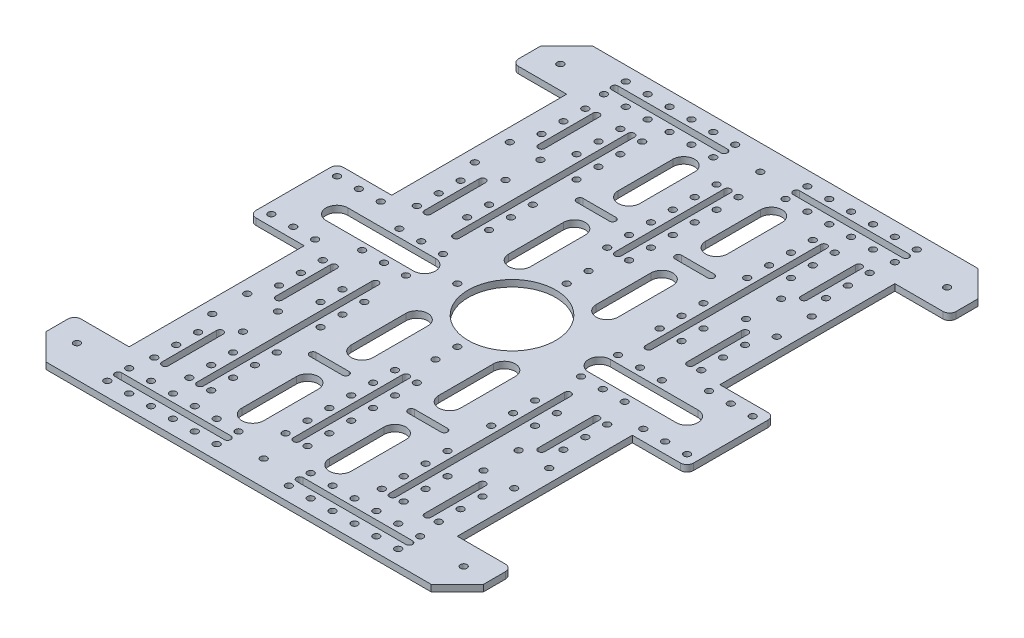
SolidWorks part; units mm, degrees
ref_plane "Front Plane" through (0, 0, 0) normal (0, 0, 1) x (1, 0, 0)
ref_plane "Top Plane" through (0, 0, 0) normal (0, 1, 0) x (1, 0, 0)
ref_plane "Right Plane" through (0, 0, 0) normal (1, 0, 0) x (0, 0, -1)
sketch "Sketch1" plane through (0, 0, 0) normal (0, 1, 0) x (1, 0, 0)
  line L0 (-100, 113) -> (-88, 125)
  line L1 (-88, 125) -> (88, 125)
  line L2 (-100, 113) -> (-100, 103)
  line L3 (-88, -125) -> (88, -125)
  line L4 (100, 113) -> (100, 103)
  line L5 (-75, 60) -> (-45.5, 60) construction
  line L7 (-100, -113) -> (-88, -125)
  line L8 (88, 125) -> (100, 113)
  line L9 (88, -125) -> (100, -113)
  line L10 (0, 125) -> (0, -125) construction
  line L11 (-100, 0) -> (100, 0) construction
  line L12 (-66.5, 113.5) -> (-16.5, 113.5) construction
  line L13 (-66.5, 115) -> (-16.5, 115)
  line L14 (-66.5, 112) -> (-16.5, 112)
  line L15 (0, 98.5) -> (0, 48.5) construction
  line L16 (1.5, 98.5) -> (1.5, 48.5)
  line L17 (-1.5, 98.5) -> (-1.5, 48.5)
  line L18 (-44, 98.5) -> (-44, 18.5) construction
  line L19 (-97, 100) -> (-75, 100)
  line L21 (-97, 20) -> (-75, 20)
  line L22 (-75, 100) -> (-75, 20)
  line L23 (-42.5, 98.5) -> (-42.5, 18.5)
  line L24 (-45.5, 98.5) -> (-45.5, 18.5)
  line L25 (-20, 98.5) -> (-20, 73.5) construction
  line L26 (-15, 98.5) -> (-15, 73.5)
  line L27 (-25, 98.5) -> (-25, 73.5)
  line L28 (-20, 48.5) -> (-20, 23.5) construction
  line L29 (-15, 48.5) -> (-15, 23.5)
  line L30 (-25, 48.5) -> (-25, 23.5)
  line L31 (-80, 0) -> (-40, 0) construction
  line L32 (-80, 5) -> (-40, 5)
  line L33 (-80, -5) -> (-40, -5)
  line L34 (-30, 61) -> (-15, 61) construction
  line L37 (-30, 62.5) -> (-15, 62.5)
  line L38 (-30, 59.5) -> (-15, 59.5)
  line L39 (100, 17) -> (100, -17)
  line L40 (-60, 98.5) -> (-60, 73.5) construction
  line L41 (-58.5, 98.5) -> (-58.5, 73.5)
  line L42 (-61.5, 98.5) -> (-61.5, 73.5)
  line L43 (-60, 21.5) -> (-60, 46.5) construction
  line L44 (-58.5, 21.5) -> (-58.5, 46.5)
  line L45 (-61.5, 21.5) -> (-61.5, 46.5)
  line L46 (-100, 17) -> (-100, -17)
  line L47 (-75, -100) -> (-75, -20)
  line L48 (-97, -20) -> (-75, -20)
  line L50 (-97, -100) -> (-75, -100)
  line L51 (-100, -113) -> (-88, -125)
  line L52 (-60, -21.5) -> (-60, -46.5) construction
  line L53 (-58.5, -21.5) -> (-58.5, -46.5)
  line L54 (-61.5, -21.5) -> (-61.5, -46.5)
  line L55 (-60, -98.5) -> (-60, -73.5) construction
  line L56 (-58.5, -98.5) -> (-58.5, -73.5)
  line L57 (-61.5, -98.5) -> (-61.5, -73.5)
  line L58 (-30, -61) -> (-15, -61) construction
  line L59 (-30, -62.5) -> (-15, -62.5)
  line L60 (-30, -59.5) -> (-15, -59.5)
  line L61 (-20, -48.5) -> (-20, -23.5) construction
  line L62 (-15, -48.5) -> (-15, -23.5)
  line L63 (-25, -48.5) -> (-25, -23.5)
  line L64 (-20, -98.5) -> (-20, -73.5) construction
  line L65 (-15, -98.5) -> (-15, -73.5)
  line L66 (-25, -98.5) -> (-25, -73.5)
  line L67 (-44, -98.5) -> (-44, -18.5) construction
  line L68 (-42.5, -98.5) -> (-42.5, -18.5)
  line L69 (-45.5, -98.5) -> (-45.5, -18.5)
  line L70 (0, -98.5) -> (0, -48.5) construction
  line L71 (1.5, -98.5) -> (1.5, -48.5)
  line L72 (-1.5, -98.5) -> (-1.5, -48.5)
  line L73 (-66.5, -113.5) -> (-16.5, -113.5) construction
  line L74 (-66.5, -115) -> (-16.5, -115)
  line L75 (-66.5, -112) -> (-16.5, -112)
  line L77 (100, -103) -> (100, -113)
  line L78 (100, -113) -> (88, -125)
  line L79 (97, -100) -> (75, -100)
  line L81 (97, -20) -> (75, -20)
  line L82 (75, -100) -> (75, -20)
  line L83 (75, 100) -> (75, 20)
  line L84 (97, 20) -> (75, 20)
  line L86 (97, 100) -> (75, 100)
  line L87 (100, -113) -> (88, -125)
  line L88 (100, 113) -> (100, 100)
  line L89 (100, 113) -> (88, 125)
  line L90 (66.5, -113.5) -> (16.5, -113.5) construction
  line L91 (66.5, -115) -> (16.5, -115)
  line L92 (66.5, -112) -> (16.5, -112)
  line L93 (44, -98.5) -> (44, -18.5) construction
  line L94 (42.5, -98.5) -> (42.5, -18.5)
  line L95 (45.5, -98.5) -> (45.5, -18.5)
  line L96 (20, -98.5) -> (20, -73.5) construction
  line L97 (15, -98.5) -> (15, -73.5)
  line L98 (25, -98.5) -> (25, -73.5)
  line L99 (20, -48.5) -> (20, -23.5) construction
  line L100 (15, -48.5) -> (15, -23.5)
  line L101 (25, -48.5) -> (25, -23.5)
  line L102 (30, -61) -> (15, -61) construction
  line L103 (30, -62.5) -> (15, -62.5)
  line L104 (30, -59.5) -> (15, -59.5)
  line L105 (60, -98.5) -> (60, -73.5) construction
  line L106 (58.5, -98.5) -> (58.5, -73.5)
  line L107 (61.5, -98.5) -> (61.5, -73.5)
  line L108 (60, -21.5) -> (60, -46.5) construction
  line L109 (58.5, -21.5) -> (58.5, -46.5)
  line L110 (61.5, -21.5) -> (61.5, -46.5)
  line L111 (60, 21.5) -> (60, 46.5) construction
  line L112 (58.5, 21.5) -> (58.5, 46.5)
  line L113 (61.5, 21.5) -> (61.5, 46.5)
  line L114 (60, 98.5) -> (60, 73.5) construction
  line L115 (58.5, 98.5) -> (58.5, 73.5)
  line L116 (61.5, 98.5) -> (61.5, 73.5)
  line L117 (30, 61) -> (15, 61) construction
  line L118 (30, 62.5) -> (15, 62.5)
  line L119 (30, 59.5) -> (15, 59.5)
  line L120 (80, 0) -> (40, 0) construction
  line L121 (80, 5) -> (40, 5)
  line L122 (80, -5) -> (40, -5)
  line L123 (20, 48.5) -> (20, 23.5) construction
  line L124 (15, 48.5) -> (15, 23.5)
  line L125 (25, 48.5) -> (25, 23.5)
  line L126 (20, 98.5) -> (20, 73.5) construction
  line L127 (15, 98.5) -> (15, 73.5)
  line L128 (25, 98.5) -> (25, 73.5)
  line L129 (44, 98.5) -> (44, 18.5) construction
  line L130 (42.5, 98.5) -> (42.5, 18.5)
  line L131 (45.5, 98.5) -> (45.5, 18.5)
  line L132 (66.5, 113.5) -> (16.5, 113.5) construction
  line L133 (66.5, 115) -> (16.5, 115)
  line L134 (66.5, 112) -> (16.5, 112)
  line L135 (-100, -103) -> (-100, -113)
  line L136 (100, 20) -> (100, -20)
  line L137 (100, -100) -> (100, -113)
  arc A0 (-66.5, 115) -> (-66.5, 112) centre (-66.5, 113.5) ccw
  arc A1 (-16.5, 112) -> (-16.5, 115) centre (-16.5, 113.5) ccw
  circle A3 centre (0, 113.5) radius 1.5
  arc A4 (1.5, 98.5) -> (-1.5, 98.5) centre (0, 98.5) ccw
  arc A5 (-1.5, 48.5) -> (1.5, 48.5) centre (0, 48.5) ccw
  arc A6 (-42.5, 98.5) -> (-45.5, 98.5) centre (-44, 98.5) ccw
  arc A7 (-45.5, 18.5) -> (-42.5, 18.5) centre (-44, 18.5) ccw
  circle A8 centre (0, 0) radius 20
  arc A9 (-15, 98.5) -> (-25, 98.5) centre (-20, 98.5) ccw
  arc A10 (-25, 73.5) -> (-15, 73.5) centre (-20, 73.5) ccw
  arc A11 (-15, 48.5) -> (-25, 48.5) centre (-20, 48.5) ccw
  arc A12 (-25, 23.5) -> (-15, 23.5) centre (-20, 23.5) ccw
  arc A13 (-80, 5) -> (-80, -5) centre (-80, 0) ccw
  arc A14 (-40, -5) -> (-40, 5) centre (-40, 0) ccw
  arc A17 (-30, 62.5) -> (-30, 59.5) centre (-30, 61) ccw
  arc A18 (-15, 59.5) -> (-15, 62.5) centre (-15, 61) ccw
  circle A19 centre (-69, 68) radius 1.5
  circle A20 centre (-69, 52) radius 1.5
  circle A21 centre (-55, 68) radius 1.5
  circle A22 centre (-55, 52) radius 1.5
  circle A23 centre (-88.3813, 110.4766) radius 1.5
  circle A24 centre (-49, 98.5) radius 1.5
  circle A25 centre (-49, 88.5) radius 1.5
  circle A26 centre (-49, 78.5) radius 1.5
  circle A30 centre (-49, 38.5) radius 1.5
  circle A31 centre (-49, 28.5) radius 1.5
  circle A33 centre (-39, 88.5) radius 1.5
  circle A34 centre (-39, 78.5) radius 1.5
  circle A35 centre (-39, 68.5) radius 1.5
  circle A37 centre (-39, 48.5) radius 1.5
  circle A38 centre (-39, 38.5) radius 1.5
  circle A39 centre (-39, 28.5) radius 1.5
  circle A41 centre (-39, 98.5) radius 1.5
  circle A42 centre (-66.5, 108.5) radius 1.5
  circle A43 centre (-56.5, 108.5) radius 1.5
  circle A44 centre (-46.5, 108.5) radius 1.5
  circle A45 centre (-36.5, 108.5) radius 1.5
  circle A46 centre (-26.5, 108.5) radius 1.5
  circle A47 centre (-16.5, 108.5) radius 1.5
  circle A48 centre (-56.5, 118.5) radius 1.5
  circle A49 centre (-46.5, 118.5) radius 1.5
  circle A50 centre (-36.5, 118.5) radius 1.5
  circle A51 centre (-26.5, 118.5) radius 1.5
  circle A52 centre (-16.5, 118.5) radius 1.5
  circle A53 centre (-66.5, 118.5) radius 1.5
  circle A54 centre (-5, 98.5) radius 1.5
  circle A61 centre (-5, 88.5) radius 1.5
  circle A62 centre (-5, 78.5) radius 1.5
  circle A63 centre (-5, 68.5) radius 1.5
  circle A64 centre (-5, 58.5) radius 1.5
  circle A65 centre (-5, 48.5) radius 1.5
  circle A66 centre (-95, 15) radius 1.5
  circle A67 centre (-85, 15) radius 1.5
  circle A68 centre (-75, 15) radius 1.5
  arc A72 (-58.5, 98.5) -> (-61.5, 98.5) centre (-60, 98.5) ccw
  arc A73 (-61.5, 73.5) -> (-58.5, 73.5) centre (-60, 73.5) ccw
  circle A74 centre (-65, 98.5) radius 1.5
  circle A75 centre (-65, 88.5) radius 1.5
  circle A76 centre (-65, 78.5) radius 1.5
  arc A77 (-58.5, 21.5) -> (-61.5, 21.5) centre (-60, 21.5) cw
  arc A78 (-61.5, 46.5) -> (-58.5, 46.5) centre (-60, 46.5) cw
  circle A79 centre (-65, 21.5) radius 1.5
  circle A80 centre (-65, 31.5) radius 1.5
  circle A81 centre (-65, 41.5) radius 1.5
  circle A82 centre (5, 98.5) radius 1.5 [skipped]
  circle A83 centre (5, 88.5) radius 1.5 [skipped]
  circle A84 centre (5, 78.5) radius 1.5 [skipped]
  circle A85 centre (5, 68.5) radius 1.5 [skipped]
  circle A86 centre (5, 58.5) radius 1.5 [skipped]
  circle A87 centre (5, 48.5) radius 1.5 [skipped]
  circle A90 centre (-60, 8.5) radius 1.5
  circle A91 centre (-50, 8.5) radius 1.5
  circle A92 centre (-40, 8.5) radius 1.5
  circle A93 centre (-40, -8.5) radius 1.5
  circle A94 centre (-50, -8.5) radius 1.5
  circle A95 centre (-60, -8.5) radius 1.5
  circle A98 centre (-65, -41.5) radius 1.5
  circle A99 centre (-65, -31.5) radius 1.5
  circle A100 centre (-65, -21.5) radius 1.5
  circle A101 centre (-65, -78.5) radius 1.5
  circle A102 centre (-65, -88.5) radius 1.5
  circle A103 centre (-65, -98.5) radius 1.5
  circle A107 centre (-75, -15) radius 1.5
  circle A108 centre (-85, -15) radius 1.5
  circle A109 centre (-95, -15) radius 1.5
  circle A110 centre (-5, -48.5) radius 1.5
  circle A111 centre (-5, -58.5) radius 1.5
  circle A112 centre (-5, -68.5) radius 1.5
  circle A113 centre (-5, -78.5) radius 1.5
  circle A114 centre (-5, -88.5) radius 1.5
  circle A115 centre (-5, -98.5) radius 1.5
  circle A116 centre (-66.5, -118.5) radius 1.5
  circle A117 centre (-16.5, -118.5) radius 1.5
  circle A118 centre (-26.5, -118.5) radius 1.5
  circle A119 centre (-36.5, -118.5) radius 1.5
  circle A120 centre (-46.5, -118.5) radius 1.5
  circle A121 centre (-56.5, -118.5) radius 1.5
  circle A122 centre (-16.5, -108.5) radius 1.5
  circle A123 centre (-26.5, -108.5) radius 1.5
  circle A124 centre (-36.5, -108.5) radius 1.5
  circle A125 centre (-46.5, -108.5) radius 1.5
  circle A126 centre (-56.5, -108.5) radius 1.5
  circle A127 centre (-66.5, -108.5) radius 1.5
  circle A128 centre (-39, -98.5) radius 1.5
  circle A130 centre (-39, -28.5) radius 1.5
  circle A131 centre (-39, -38.5) radius 1.5
  circle A132 centre (-39, -48.5) radius 1.5
  circle A134 centre (-39, -68.5) radius 1.5
  circle A135 centre (-39, -78.5) radius 1.5
  circle A136 centre (-39, -88.5) radius 1.5
  circle A138 centre (-49, -28.5) radius 1.5
  circle A139 centre (-49, -38.5) radius 1.5
  circle A143 centre (-49, -78.5) radius 1.5
  circle A144 centre (-49, -88.5) radius 1.5
  circle A145 centre (-49, -98.5) radius 1.5
  circle A146 centre (-88.3813, -110.4766) radius 1.5
  circle A147 centre (-55, -52) radius 1.5
  circle A148 centre (-55, -68) radius 1.5
  circle A149 centre (-69, -52) radius 1.5
  circle A150 centre (-69, -68) radius 1.5
  circle A151 centre (0, -113.5) radius 1.5
  arc A152 (-58.5, -21.5) -> (-61.5, -21.5) centre (-60, -21.5) ccw
  arc A153 (-61.5, -46.5) -> (-58.5, -46.5) centre (-60, -46.5) ccw
  arc A154 (-58.5, -98.5) -> (-61.5, -98.5) centre (-60, -98.5) cw
  arc A155 (-61.5, -73.5) -> (-58.5, -73.5) centre (-60, -73.5) cw
  arc A156 (-30, -62.5) -> (-30, -59.5) centre (-30, -61) cw
  arc A157 (-15, -59.5) -> (-15, -62.5) centre (-15, -61) cw
  arc A158 (-15, -48.5) -> (-25, -48.5) centre (-20, -48.5) cw
  arc A159 (-25, -23.5) -> (-15, -23.5) centre (-20, -23.5) cw
  arc A160 (-15, -98.5) -> (-25, -98.5) centre (-20, -98.5) cw
  arc A161 (-25, -73.5) -> (-15, -73.5) centre (-20, -73.5) cw
  arc A162 (-42.5, -98.5) -> (-45.5, -98.5) centre (-44, -98.5) cw
  arc A163 (-45.5, -18.5) -> (-42.5, -18.5) centre (-44, -18.5) cw
  arc A164 (1.5, -98.5) -> (-1.5, -98.5) centre (0, -98.5) cw
  arc A165 (-1.5, -48.5) -> (1.5, -48.5) centre (0, -48.5) cw
  arc A166 (-66.5, -115) -> (-66.5, -112) centre (-66.5, -113.5) cw
  arc A167 (-16.5, -112) -> (-16.5, -115) centre (-16.5, -113.5) cw
  circle A168 centre (69, -68) radius 1.5
  circle A169 centre (69, -52) radius 1.5
  circle A170 centre (55, -68) radius 1.5
  circle A171 centre (55, -52) radius 1.5
  circle A172 centre (88.3813, -110.4766) radius 1.5
  circle A173 centre (49, -98.5) radius 1.5
  circle A174 centre (49, -88.5) radius 1.5
  circle A175 centre (49, -78.5) radius 1.5
  circle A179 centre (49, -38.5) radius 1.5
  circle A180 centre (49, -28.5) radius 1.5
  circle A182 centre (39, -88.5) radius 1.5
  circle A183 centre (39, -78.5) radius 1.5
  circle A184 centre (39, -68.5) radius 1.5
  circle A186 centre (39, -48.5) radius 1.5
  circle A187 centre (39, -38.5) radius 1.5
  circle A188 centre (39, -28.5) radius 1.5
  circle A190 centre (39, -98.5) radius 1.5
  circle A191 centre (66.5, -108.5) radius 1.5
  circle A192 centre (56.5, -108.5) radius 1.5
  circle A193 centre (46.5, -108.5) radius 1.5
  circle A194 centre (36.5, -108.5) radius 1.5
  circle A195 centre (26.5, -108.5) radius 1.5
  circle A196 centre (16.5, -108.5) radius 1.5
  circle A197 centre (56.5, -118.5) radius 1.5
  circle A198 centre (46.5, -118.5) radius 1.5
  circle A199 centre (36.5, -118.5) radius 1.5
  circle A200 centre (26.5, -118.5) radius 1.5
  circle A201 centre (16.5, -118.5) radius 1.5
  circle A202 centre (66.5, -118.5) radius 1.5
  circle A203 centre (5, -98.5) radius 1.5
  circle A204 centre (5, -88.5) radius 1.5
  circle A205 centre (5, -78.5) radius 1.5
  circle A206 centre (5, -68.5) radius 1.5
  circle A207 centre (5, -58.5) radius 1.5
  circle A208 centre (5, -48.5) radius 1.5
  circle A209 centre (95, -15) radius 1.5
  circle A210 centre (85, -15) radius 1.5
  circle A211 centre (75, -15) radius 1.5
  circle A215 centre (65, -98.5) radius 1.5
  circle A216 centre (65, -88.5) radius 1.5
  circle A217 centre (65, -78.5) radius 1.5
  circle A218 centre (65, -21.5) radius 1.5
  circle A219 centre (65, -31.5) radius 1.5
  circle A220 centre (65, -41.5) radius 1.5
  circle A223 centre (60, -8.5) radius 1.5
  circle A224 centre (50, -8.5) radius 1.5
  circle A225 centre (40, -8.5) radius 1.5
  circle A226 centre (40, 8.5) radius 1.5
  circle A227 centre (50, 8.5) radius 1.5
  circle A228 centre (60, 8.5) radius 1.5
  circle A231 centre (65, 41.5) radius 1.5
  circle A232 centre (65, 31.5) radius 1.5
  circle A233 centre (65, 21.5) radius 1.5
  circle A234 centre (65, 78.5) radius 1.5
  circle A235 centre (65, 88.5) radius 1.5
  circle A236 centre (65, 98.5) radius 1.5
  circle A240 centre (75, 15) radius 1.5
  circle A241 centre (85, 15) radius 1.5
  circle A242 centre (95, 15) radius 1.5
  circle A243 centre (5, 48.5) radius 1.5
  circle A244 centre (5, 58.5) radius 1.5
  circle A245 centre (5, 68.5) radius 1.5
  circle A246 centre (5, 78.5) radius 1.5
  circle A247 centre (5, 88.5) radius 1.5
  circle A248 centre (5, 98.5) radius 1.5
  circle A249 centre (66.5, 118.5) radius 1.5
  circle A250 centre (16.5, 118.5) radius 1.5
  circle A251 centre (26.5, 118.5) radius 1.5
  circle A252 centre (36.5, 118.5) radius 1.5
  circle A253 centre (46.5, 118.5) radius 1.5
  circle A254 centre (56.5, 118.5) radius 1.5
  circle A255 centre (16.5, 108.5) radius 1.5
  circle A256 centre (26.5, 108.5) radius 1.5
  circle A257 centre (36.5, 108.5) radius 1.5
  circle A258 centre (46.5, 108.5) radius 1.5
  circle A259 centre (56.5, 108.5) radius 1.5
  circle A260 centre (66.5, 108.5) radius 1.5
  circle A261 centre (39, 98.5) radius 1.5
  circle A263 centre (39, 28.5) radius 1.5
  circle A264 centre (39, 38.5) radius 1.5
  circle A265 centre (39, 48.5) radius 1.5
  circle A267 centre (39, 68.5) radius 1.5
  circle A268 centre (39, 78.5) radius 1.5
  circle A269 centre (39, 88.5) radius 1.5
  circle A271 centre (49, 28.5) radius 1.5
  circle A272 centre (49, 38.5) radius 1.5
  circle A276 centre (49, 78.5) radius 1.5
  circle A277 centre (49, 88.5) radius 1.5
  circle A278 centre (49, 98.5) radius 1.5
  circle A279 centre (88.3813, 110.4766) radius 1.5
  circle A280 centre (55, 52) radius 1.5
  circle A281 centre (55, 68) radius 1.5
  circle A282 centre (69, 52) radius 1.5
  circle A283 centre (69, 68) radius 1.5
  arc A284 (66.5, -115) -> (66.5, -112) centre (66.5, -113.5) ccw
  arc A285 (16.5, -112) -> (16.5, -115) centre (16.5, -113.5) ccw
  arc A286 (42.5, -98.5) -> (45.5, -98.5) centre (44, -98.5) ccw
  arc A287 (45.5, -18.5) -> (42.5, -18.5) centre (44, -18.5) ccw
  arc A288 (15, -98.5) -> (25, -98.5) centre (20, -98.5) ccw
  arc A289 (25, -73.5) -> (15, -73.5) centre (20, -73.5) ccw
  arc A290 (15, -48.5) -> (25, -48.5) centre (20, -48.5) ccw
  arc A291 (25, -23.5) -> (15, -23.5) centre (20, -23.5) ccw
  arc A292 (30, -62.5) -> (30, -59.5) centre (30, -61) ccw
  arc A293 (15, -59.5) -> (15, -62.5) centre (15, -61) ccw
  arc A294 (58.5, -98.5) -> (61.5, -98.5) centre (60, -98.5) ccw
  arc A295 (61.5, -73.5) -> (58.5, -73.5) centre (60, -73.5) ccw
  arc A296 (58.5, -21.5) -> (61.5, -21.5) centre (60, -21.5) cw
  arc A297 (61.5, -46.5) -> (58.5, -46.5) centre (60, -46.5) cw
  arc A298 (58.5, 21.5) -> (61.5, 21.5) centre (60, 21.5) ccw
  arc A299 (61.5, 46.5) -> (58.5, 46.5) centre (60, 46.5) ccw
  arc A300 (58.5, 98.5) -> (61.5, 98.5) centre (60, 98.5) cw
  arc A301 (61.5, 73.5) -> (58.5, 73.5) centre (60, 73.5) cw
  arc A302 (30, 62.5) -> (30, 59.5) centre (30, 61) cw
  arc A303 (15, 59.5) -> (15, 62.5) centre (15, 61) cw
  arc A304 (80, 5) -> (80, -5) centre (80, 0) cw
  arc A305 (40, -5) -> (40, 5) centre (40, 0) cw
  arc A306 (15, 48.5) -> (25, 48.5) centre (20, 48.5) cw
  arc A307 (25, 23.5) -> (15, 23.5) centre (20, 23.5) cw
  arc A308 (15, 98.5) -> (25, 98.5) centre (20, 98.5) cw
  arc A309 (25, 73.5) -> (15, 73.5) centre (20, 73.5) cw
  arc A310 (42.5, 98.5) -> (45.5, 98.5) centre (44, 98.5) cw
  arc A311 (45.5, 18.5) -> (42.5, 18.5) centre (44, 18.5) cw
  arc A312 (66.5, 115) -> (66.5, 112) centre (66.5, 113.5) cw
  arc A313 (16.5, 112) -> (16.5, 115) centre (16.5, 113.5) cw
  arc A314 (100, 103) -> (97, 100) centre (97, 103) cw
  arc A315 (97, 20) -> (100, 17) centre (97, 17) cw
  arc A316 (100, -17) -> (97, -20) centre (97, -17) cw
  arc A317 (97, -100) -> (100, -103) centre (97, -103) cw
  arc A318 (-97, 100) -> (-100, 103) centre (-97, 103) cw
  arc A319 (-100, 17) -> (-97, 20) centre (-97, 17) cw
  arc A320 (-97, -20) -> (-100, -17) centre (-97, -17) cw
  arc A321 (-100, -103) -> (-97, -100) centre (-97, -103) cw
  circle A322 centre (0, 25) radius 1.5
  circle A323 centre (0, 35) radius 1.5
  circle A326 centre (0, -35) radius 1.5
  circle A327 centre (0, -25) radius 1.5
  circle A329 centre (-25, 0) radius 1.5
  circle A330 centre (-35, 0) radius 1.5 [skipped]
  circle A331 centre (25, 0) radius 1.5 [skipped]
  circle A332 centre (-49, 68.5) radius 1.5 [skipped]
  circle A333 centre (-49, 58.5) radius 1.5 [skipped]
  circle A334 centre (-49, 48.5) radius 1.5 [skipped]
  circle A335 centre (-39, 58.5) radius 1.5 [skipped]
  circle A336 centre (35, 0) radius 1.5 [skipped]
  circle A338 centre (-49, 18.5) radius 1.5 [skipped]
  circle A339 centre (-39, 18.5) radius 1.5 [skipped]
  point P0 (0, 0)
  point P3 (0, 0)
  point P4 (0, 0)
  point P18 (-41.5, 113.5)
  point P29 (0, 73.5)
  point P40 (-44, 58.5)
  point P49 (-20, 86)
  point P57 (-20, 36)
  point P63 (-60, 0)
  point P70 (-22.5, 61)
  point P95 (0, 0)
  point P185 (-60, 86)
  point P198 (-60, 34)
  point P345 (-60, -34)
  point P352 (-60, -86)
  point P359 (-22.5, -61)
  point P366 (-20, -36)
  point P373 (-20, -86)
  point P380 (-44, -58.5)
  point P387 (0, -73.5)
  point P394 (-41.5, -113.5)
  point P645 (41.5, -113.5)
  point P652 (44, -58.5)
  point P659 (20, -86)
  point P666 (20, -36)
  point P673 (22.5, -61)
  point P680 (60, -86)
  point P687 (60, -34)
  point P694 (60, 34)
  point P701 (60, 86)
  point P708 (22.5, 61)
  point P715 (60, 0)
  point P722 (20, 36)
  point P729 (20, 86)
  point P736 (44, 58.5)
  point P743 (41.5, 113.5)
  point P754 (-100, 100)
  point P757 (-100, 20)
  point P760 (-100, -20)
  point P763 (-100, -100)
  point P783 (0, 0)
  dimension "D3" = 1.5
  dimension "D5" = 15
  dimension "D7" = 3
  dimension "D8" = 11.5
  dimension "D11" = 1.5
  dimension "D15" = 15
  dimension "D19" = 1.5
  dimension "D22" = 40
  dimension "D24" = 5
  dimension "D27" = 15
  dimension "D29" = 5
  dimension "D30" = 15
  dimension "D31" = 15
  dimension "D32" = 7.5
  dimension "D35" = 1.5
  dimension "D37" = 3
  dimension "D45" = 3
  dimension "D50" = 3
  dimension "D54" = 3
  dimension "D56" = 2
  dimension "D58" = 3
  dimension "D61" = 3
  dimension "D62" = 1.5
  dimension "D64" = 3
  dimension "D70" = 3
  dimension "D71" = 3
  dimension "D72" = 5
  dimension "D9" = 50
  dimension "D4" = 50
  dimension "D6" = 10
  dimension "D14" = 50
  dimension "D16" = 80
  dimension "D18" = 25
  dimension "D20" = 80
  dimension "D21" = 15
  dimension "D23" = 31
  dimension "D25" = 25
  dimension "D28" = 2
  dimension "D33" = 15
  dimension "D34" = 25
  dimension "D36" = 15
  dimension "D38" = 16
  dimension "D39" = 14
  dimension "D41" = 14
  dimension "D42" = 6
  dimension "D46" = 5
  dimension "D47" = 5
  dimension "D51" = 5
  dimension "D55" = 5
  dimension "D59" = 5
  dimension "D60" = 5
  dimension "D63" = 25
  dimension "D65" = 5
  dimension "D10" = 10
  dimension "D48" = 9
  dimension "D49" = 2
  dimension "D52" = 6
  dimension "D53" = 2
  dimension "D57" = 6
  dimension "D66" = 3
  dimension "D73" = 2
  dimension "D74" = 4
extrude "Boss-Extrude1" add sketch "Sketch1" along normal blind 3 contours A321 L135 L7 L3 L9 L77 A317 L79 L82 L81 A316 L39 A315 L84 L83 L86 A314 L4 L8 L1 L0 L2 A318 L19 L22 L21 A319 L46 A320 L48 L47 L50 A299 L113 A298 L112 A295 L107 A294 L106 A293 L104 A292 L103 A291 L101 A290
